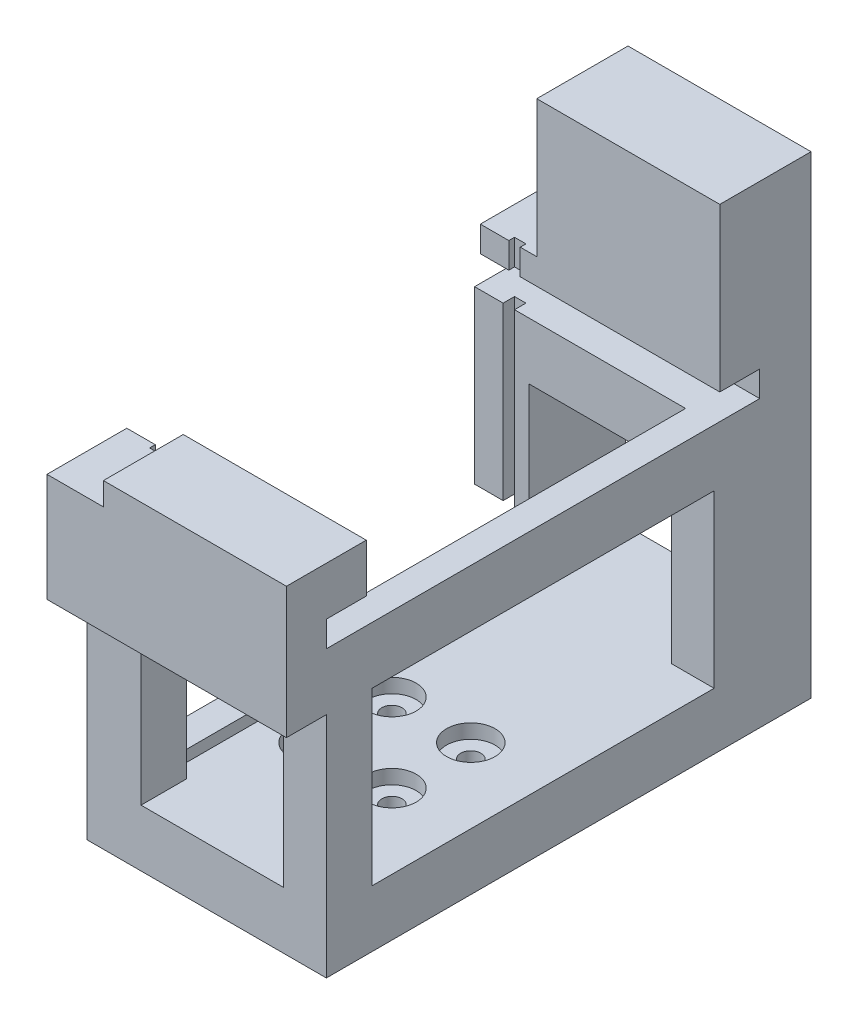
SolidWorks part; units mm, degrees
ref_plane "Front Plane" through (0, 0, 0) normal (0, 0, 1) x (1, 0, 0)
ref_plane "Top Plane" through (0, 0, 0) normal (0, 1, 0) x (1, 0, 0)
ref_plane "Right Plane" through (0, 0, 0) normal (1, 0, 0) x (0, 0, -1)
sketch "Sketch1" plane through (0, 0, 0) normal (0, 1, 0) x (1, 0, 0)
  line L1 (0, 0) -> (40, 0)
  line L2 (0, 0) -> (0, 76)
  line L3 (0, 76) -> (40, 76)
  line L4 (40, 0) -> (40, 76)
  dimension "D1" = 76
  dimension "D2" = 40
extrude "Boss-Extrude1" add sketch "Sketch1" along normal blind 10
sketch "Sketch2" plane through (0, 10, 0) normal (0, 1, 0) x (1, 0, 0)
  line L0 (0, 76) -> (0, 0) construction
  line L1 (5, 68) -> (35, 68)
  line L2 (5, 68) -> (5, 8)
  line L3 (5, 8) -> (35, 8)
  line L4 (35, 68) -> (35, 8)
  line L5 (40, 0) -> (40, 76) construction
  line L6 (40, 76) -> (0, 76) construction
  line L7 (0, 0) -> (40, 0) construction
  line L9 (0, 76) -> (40, 76)
  line L10 (0, 76) -> (0, 0)
  line L11 (0, 0) -> (40, 0)
  line L12 (40, 76) -> (40, 0)
  dimension "D1" = 5
  dimension "D2" = 5
  dimension "D3" = 8
  dimension "D4" = 8
extrude "Boss-Extrude2" add sketch "Sketch2" along normal blind 40
sketch "Sketch3" plane through (0, 0, 0) normal (0, 0, 1) x (1, 0, 0)
  line L0 (0, 0) -> (40, 0) construction
  line L1 (7.5, 40) -> (32.5, 40)
  line L2 (7.5, 40) -> (7.5, 10)
  line L3 (7.5, 10) -> (32.5, 10)
  line L4 (32.5, 40) -> (32.5, 10)
  line L5 (0, 50) -> (0, 0) construction
  line L6 (40, 50) -> (40, 0) construction
  line L7 (0, 50) -> (40, 50) construction
  dimension "D1" = 10
  dimension "D2" = 7.5
  dimension "D3" = 7.5
  dimension "D4" = 10
extrude "Cut-Extrude1" cut sketch "Sketch3" against normal through all
sketch "Sketch4" plane through (0, 0, 0) normal (-1, 0, 0) x (0, 0, 1)
  line L0 (-76, 50) -> (0, 50) construction
  line L1 (-68, 40) -> (-8, 40)
  line L2 (-68, 40) -> (-68, 10)
  line L3 (-68, 10) -> (-8, 10)
  line L4 (-8, 40) -> (-8, 10)
  line L5 (-76, 0) -> (0, 0) construction
  line L6 (-76, 50) -> (-76, 0) construction
  line L7 (0, 50) -> (0, 0) construction
  dimension "D1" = 10
  dimension "D2" = 10
  dimension "D3" = 8
  dimension "D4" = 8
extrude "Cut-Extrude2" cut sketch "Sketch4" against normal through all
sketch "Sketch9" plane through (0, 0, 0) normal (0, -1, 0) x (1, 0, 0)
  line L0 (20, -31.5) -> (20, -41.279) construction
  line L1 (20, -41.279) -> (13.0852, -38.4148) construction
  line L2 (13.0852, -38.4148) -> (10.221, -31.5) construction
  line L3 (10.221, -31.5) -> (13.0852, -24.5852) construction
  line L4 (13.0852, -24.5852) -> (20, -21.721) construction
  line L5 (20, -21.721) -> (26.9148, -24.5852) construction
  line L6 (26.9148, -24.5852) -> (29.779, -31.5) construction
  line L7 (29.779, -31.5) -> (26.9148, -38.4148) construction
  line L8 (26.9148, -38.4148) -> (20, -41.279) construction
  line L9 (20, -31.5) -> (13.0852, -38.4148) construction
  line L10 (20, -31.5) -> (10.221, -31.5) construction
  line L11 (10.221, -31.5) -> (13.0852, -24.5852) construction
  line L12 (13.0852, -24.5852) -> (20, -31.5) construction
  line L13 (20, -31.5) -> (20, -21.721) construction
  line L14 (20, -21.721) -> (26.9148, -24.5852) construction
  line L15 (26.9148, -24.5852) -> (20, -31.5) construction
  line L16 (20, -31.5) -> (29.779, -31.5) construction
  line L17 (29.779, -31.5) -> (26.9148, -38.4148) construction
  line L18 (26.9148, -38.4148) -> (20, -31.5) construction
  line L19 (20, -31.5) -> (20, -41.279) construction
  line L20 (20, -41.279) -> (26.9148, -38.4148) construction
  line L21 (0, 0) -> (40, 0) construction
  line L22 (40, 0) -> (40, -76) construction
  circle A0 centre (20, -31.5) radius 6.3627
  circle A1 centre (20, -41.279) radius 1.778
  circle A2 centre (13.0852, -38.4148) radius 1.778
  circle A3 centre (10.221, -31.5) radius 1.778
  circle A4 centre (13.0852, -24.5852) radius 1.778
  circle A5 centre (20, -21.721) radius 1.778
  circle A6 centre (26.9148, -24.5852) radius 1.778
  circle A7 centre (26.9148, -38.4148) radius 1.778
  circle A8 centre (29.779, -31.5) radius 1.778
  circle A9 centre (26.9148, -24.5852) radius 1.778
  dimension "D1" = 31.5
  dimension "D5" = 7.4845
  dimension "D2" = 20
  dimension "D3" = 9.779
  dimension "D4" = 9.779
  dimension "D6" = 7.4845
extrude "Cut-Extrude4" cut sketch "Sketch9" against normal blind 40 contours A7 | A4 | A6 | A8 | A2
sketch "Sketch12" plane through (0, 10, 0) normal (0, 1, 0) x (1, 0, 0)
  circle A0 centre (29.779, 31.5) radius 1.778
extrude "Boss-Extrude4" add sketch "Sketch12" against normal up to surface (10 mm away) up to face at (13.0852, 0, -40.1928)
sketch "Sketch13" plane through (0, 0, 0) normal (0, 0, 1) x (1, 0, 0)
  line L1 (0, 50) -> (40, 50)
  line L2 (0, 50) -> (0, 40)
  line L3 (0, 40) -> (40, 40)
  line L4 (40, 50) -> (40, 40)
extrude "Boss-Extrude5" add sketch "Sketch13" along normal blind 7
sketch "Sketch14" plane through (0, 0, -76) normal (0, 0, -1) x (-1, 0, 0)
  line L0 (0, 50) -> (0, 0) construction
  line L1 (-40, 50) -> (0, 50)
  line L2 (-40, 50) -> (-40, 40)
  line L3 (-40, 40) -> (0, 40)
  line L4 (0, 50) -> (0, 40)
  line L5 (-32.5, 40) -> (-7.5, 40) construction
  dimension "D1" = 0
extrude "Boss-Extrude6" add sketch "Sketch14" along normal blind 7
sketch "Sketch16" plane through (0, 50, 0) normal (0, 1, 0) x (1, 0, 0)
  line L0 (40, -7) -> (40, 83) construction
  line L1 (0, 83) -> (40, 83)
  line L2 (0, 83) -> (0, 76)
  line L3 (0, 76) -> (40, 76)
  line L4 (40, 83) -> (40, 76)
  line L6 (0, -7) -> (40, -7)
  line L7 (0, -7) -> (0, 0)
  line L8 (0, 0) -> (40, 0)
  line L9 (40, -7) -> (40, 0)
  dimension "D1" = 7
  dimension "D2" = 7
extrude "Boss-Extrude7" add sketch "Sketch16" along normal blind 4.5
sketch "Sketch17" plane through (0, 0, -83) normal (0, 0, -1) x (-1, 0, 0)
  line L1 (-40, 54.5) -> (0, 54.5)
  line L2 (-40, 54.5) -> (-40, 59)
  line L3 (-40, 59) -> (0, 59)
  line L4 (0, 54.5) -> (0, 59)
  dimension "D1" = 4.5
extrude "Boss-Extrude8" add sketch "Sketch17" against normal blind 14
sketch "Sketch18" plane through (0, 0, 7) normal (0, 0, 1) x (1, 0, 0)
  line L1 (0, 54.5) -> (40, 54.5)
  line L2 (0, 54.5) -> (0, 59)
  line L3 (0, 59) -> (40, 59)
  line L4 (40, 54.5) -> (40, 59)
extrude "Boss-Extrude9" add sketch "Sketch18" against normal blind 14
sketch "Sketch19" plane through (0, 0, -83) normal (0, 0, -1) x (-1, 0, 0)
  line L1 (-40, 40) -> (0, 40)
  line L2 (-40, 40) -> (-40, 59)
  line L3 (-40, 59) -> (0, 59)
  line L4 (0, 40) -> (0, 59)
extrude "Boss-Extrude10" add sketch "Sketch19" along normal blind 2
sketch "Sketch20" plane through (0, 0, -76) normal (0, 0, -1) x (-1, 0, 0)
  line L0 (0, 40) -> (0, 0)
  line L1 (0, 0) -> (-40, 0)
  line L2 (-40, 0) -> (-40, 40)
  line L3 (-40, 40) -> (-32.5, 40)
  line L4 (-32.5, 40) -> (-32.5, 10)
  line L5 (-32.5, 10) -> (-7.5, 10)
  line L6 (-7.5, 10) -> (-7.5, 40)
  line L7 (-7.5, 40) -> (0, 40)
extrude "Boss-Extrude11" add sketch "Sketch20" along normal up to vertex (9 mm away) up to point (40, 40, -85)
sketch "Sketch21" plane through (0, 0, 0) normal (-1, 0, 0) x (0, 0, 1)
  line L0 (-68, 10) -> (-77, 10)
  line L1 (-77, 10) -> (-77, 20)
  line L2 (-77, 20) -> (-68, 20)
  line L3 (-68, 40) -> (-68, 10) construction
  line L4 (-68, 20) -> (-68, 10)
  dimension "D1" = 10
  dimension "D2" = 9
extrude "Cut-Extrude6" cut sketch "Sketch21" against normal up to vertex
sketch "Sketch23" plane through (0, 0, 0) normal (-1, 0, 0) x (0, 0, 1)
  line L0 (-69, 59) -> (-69, 54.5)
  line L1 (-69, 54.5) -> (-76, 54.5)
  line L2 (-76, 54.5) -> (-76, 50)
  line L3 (-76, 50) -> (0, 50)
  line L4 (0, 50) -> (0, 54.5)
  line L5 (0, 54.5) -> (-7, 54.5)
  line L6 (-7, 54.5) -> (-7, 59)
  line L7 (-7, 59) -> (7, 59)
  line L8 (7, 59) -> (7, 40)
  line L9 (7, 40) -> (0, 40)
  line L10 (0, 40) -> (0, 0)
  line L11 (0, 0) -> (-85, 0)
  line L12 (-85, 0) -> (-85, 59)
  line L13 (-85, 59) -> (-69, 59)
  line L14 (-68, 40) -> (-68, 20)
  line L15 (-68, 20) -> (-77, 20)
  line L17 (-85, 10) -> (-68, 10) construction
  line L18 (-76.5, 10) -> (-8, 10)
  line L19 (-8, 10) -> (-8, 40)
  line L20 (-8, 40) -> (-68, 40)
  line L21 (-77, 20) -> (-77, 10)
  line L22 (-77, 10) -> (-76.5, 10)
extrude "Boss-Extrude13" add sketch "Sketch23" along normal blind 2
sketch "Sketch25" plane through (0, 59, 0) normal (0, 1, 0) x (1, 0, 0)
  line L0 (5, 8) -> (-2, 8) construction
  line L1 (5, 70) -> (3, 70)
  line L2 (5, 70) -> (5, 6)
  line L3 (5, 6) -> (3, 6)
  line L4 (3, 70) -> (3, 6)
  line L5 (-2, 69) -> (40, 69) construction
  line L6 (5, 68) -> (5, 8) construction
  dimension "D1" = 2
  dimension "D2" = 1
  dimension "D3" = 2
  dimension "D4" = 2
extrude "Cut-Extrude7" cut sketch "Sketch25" against normal up to vertex
sketch "Sketch26" plane through (0, 50, 0) normal (0, 1, 0) x (1, 0, 0)
  line L1 (5, 70) -> (3, 70)
  line L2 (5, 70) -> (5, 6)
  line L3 (5, 6) -> (3, 6)
  line L4 (3, 70) -> (3, 6)
extrude "Cut-Extrude8" cut sketch "Sketch26" against normal blind 42
sketch "Sketch27" plane through (-2, 0, 0) normal (-1, 0, 0) x (0, 0, 1)
  line L0 (0, 50) -> (-76, 50) construction
  line L1 (-68, 40) -> (-8, 40)
  line L2 (-68, 40) -> (-68, 50)
  line L3 (-68, 50) -> (-8, 50)
  line L4 (-8, 40) -> (-8, 50)
extrude "Cut-Extrude10" cut sketch "Sketch27" against normal blind 10
sketch "Sketch28" plane through (0, 59, 0) normal (0, 1, 0) x (1, 0, 0)
  line L0 (5, 69) -> (40, 69) construction
  line L1 (7.8989, 69) -> (40, 69)
  line L2 (7.8989, 69) -> (7.8989, 85)
  line L3 (7.8989, 85) -> (40, 85)
  line L4 (40, 69) -> (40, 85)
  line L5 (40, -7) -> (-2, -7) construction
  line L6 (40, 7) -> (7.8989, 7)
  line L7 (40, 7) -> (40, -7)
  line L8 (40, -7) -> (7.8989, -7)
  line L9 (7.8989, 7) -> (7.8989, -7)
extrude "Boss-Extrude14" add sketch "Sketch28" along normal blind 24 contours L2 L1 L4 L3
sketch "Sketch29" plane through (0, 59, 0) normal (0, 1, 0) x (1, 0, 0)
  line L0 (40, 7) -> (5, 7) construction
  line L1 (40, -7) -> (7.8989, -7)
  line L2 (40, -7) -> (40, 7)
  line L3 (40, 7) -> (7.8989, 7)
  line L4 (7.8989, -7) -> (7.8989, 7)
extrude "Boss-Extrude15" add sketch "Sketch29" along normal blind 4
sketch "Sketch30" plane through (0, 10, 0) normal (0, 1, 0) x (1, 0, 0)
  circle A0 centre (13.0852, 24.5852) radius 4.25
  circle A1 centre (13.0852, 38.4148) radius 4.25
  circle A2 centre (26.9148, 38.4148) radius 4.25
  circle A3 centre (26.9148, 24.5852) radius 4.25
  dimension "D1" = 8.5
  dimension "D2" = 8.5
  dimension "D3" = 8.5
  dimension "D4" = 8.5
extrude "Cut-Extrude11" cut sketch "Sketch30" against normal blind 2.5
